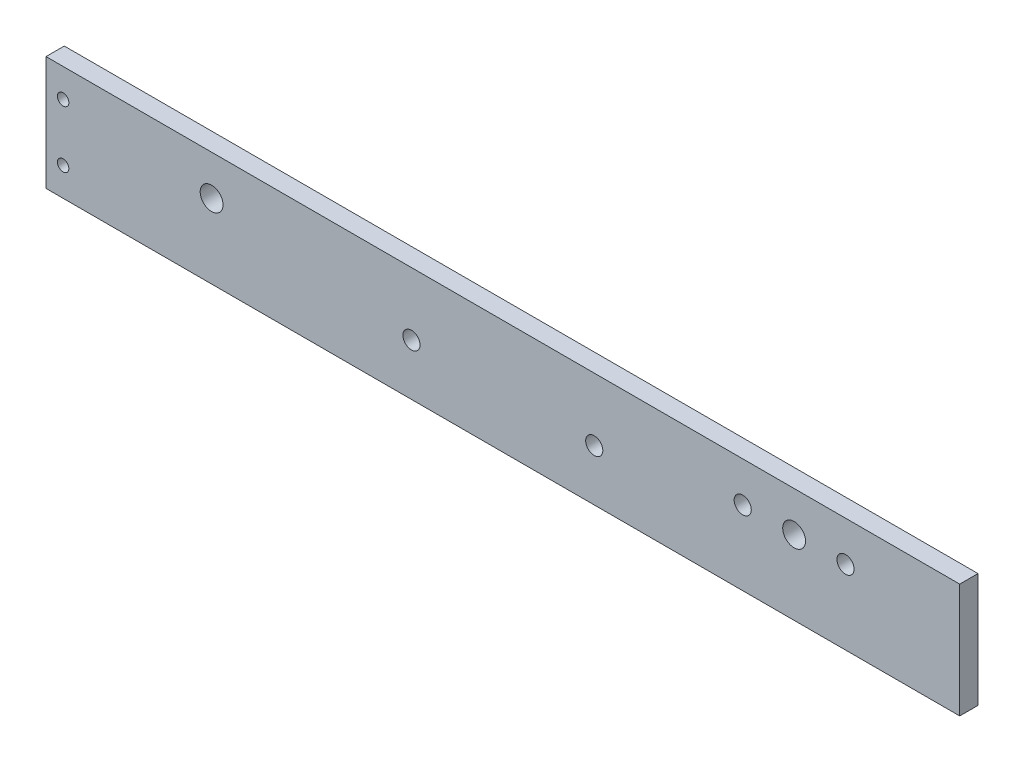
SolidWorks part; units mm, degrees
material "Balsa"
ref_plane "Front Plane" through (0, 0, 0) normal (0, 0, 1) x (1, 0, 0)
ref_plane "Top Plane" through (0, 0, 0) normal (0, 1, 0) x (1, 0, 0)
ref_plane "Right Plane" through (0, 0, 0) normal (1, 0, 0) x (0, 0, -1)
ref_plane "Plane1" through (0, 0, 10) normal (0, 0, 1) x (1, 0, 0)
sketch "Sketch2" plane through (0, -10, 10) normal (0, 0, -1) x (1, 0, 0)
  line L1 (0, -10) -> (160, -10)
  line L2 (0, -10) -> (0, 10)
  line L3 (0, 10) -> (160, 10)
  line L4 (160, -10) -> (160, 10)
  dimension "D1" = 20
  dimension "D2" = 160
extrude "Boss-Extrude1" add sketch "Sketch2" along normal blind 3.2
sketch "Sketch4" plane through (0, 0, 0) normal (0, 1, 0) x (1, 0, 0)
  line L0 (0, -10) -> (160, -10) construction
  line L1 (0, -6.8) -> (80, -6.8)
  line L2 (0, -6.8) -> (0, -10)
  line L3 (0, -10) -> (80, -10)
  line L4 (80, -6.8) -> (80, -10)
  line L5 (160, -6.8) -> (160, -10) construction
  dimension "D1" = 80
  dimension "D2" = 80
sketch "Sketch5" plane through (0, 0, 10) normal (0, 0, 1) x (1, 0, 0)
  line L0 (102, 2.15) -> (102, -20)
  line L1 (102, 0) -> (102, 4.3) construction
  line L2 (160, -20) -> (0, -20) construction
  line L3 (58, 2.15) -> (58, -20)
  line L4 (58, 0) -> (58, 4.3) construction
  line L7 (29, -7) -> (131, -7)
  line L9 (0, 0) -> (160, 0) construction
  circle A0 centre (131, -7) radius 2
  circle A1 centre (29, -7) radius 2
  dimension "D1" = 7
extrude "Cut-Extrude1" cut sketch "Sketch5" against normal through all both and the other way through all contours A0 | A1
sketch "Sketch6" plane through (0, 0, 10) normal (0, 0, 1) x (1, 0, 0)
  circle A0 centre (96, -11) radius 1.5
  circle A1 centre (64, -11) radius 1.5
  dimension "D1" = 32
extrude "Cut-Extrude2" cut sketch "Sketch6" against normal blind 10
sketch "Sketch7" plane through (0, 0, 10) normal (0, 0, 1) x (1, 0, 0)
  circle A0 centre (3, -15) radius 1
  circle A1 centre (3, -5) radius 1
  dimension "D1" = 2
extrude "Cut-Extrude3" cut sketch "Sketch7" against normal through all both and the other way through all
sketch "Sketch8" plane through (0, 0, 10) normal (0, 0, 1) x (1, 0, 0)
  circle A0 centre (140, -7) radius 1.5
  circle A1 centre (122, -7) radius 1.5
extrude "Cut-Extrude4" cut sketch "Sketch8" against normal blind 10
